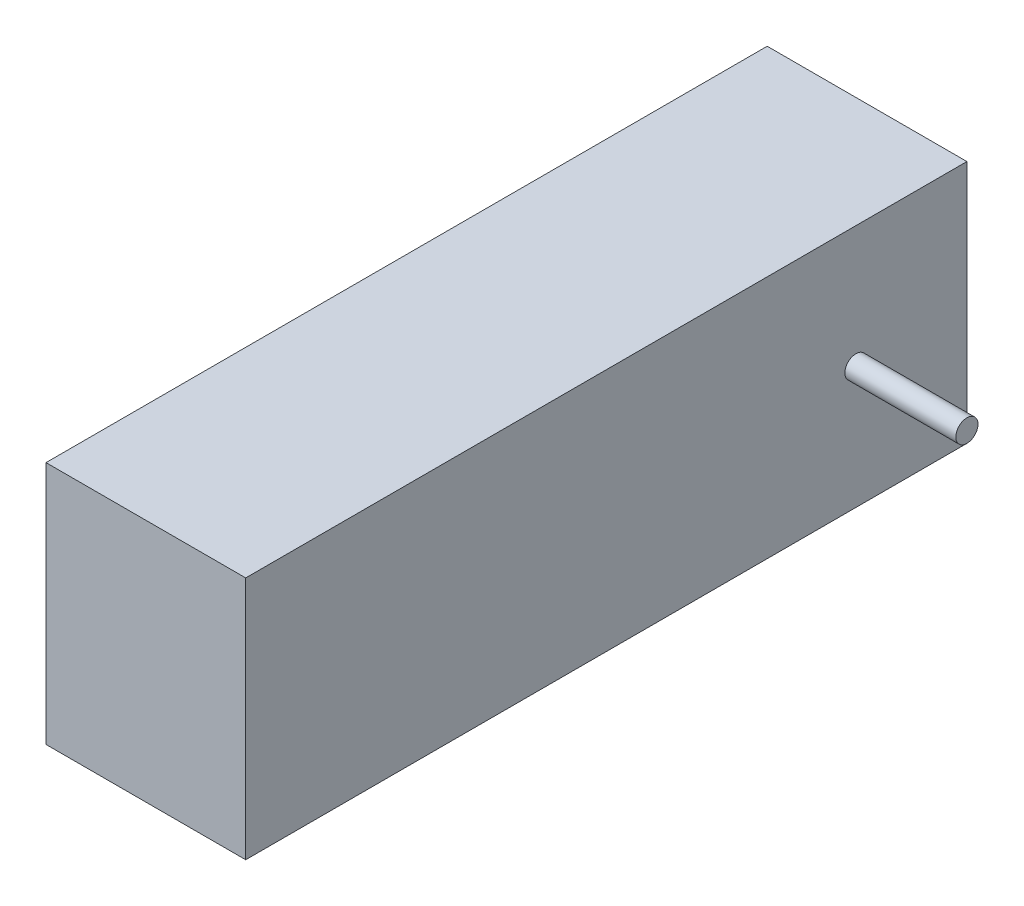
SolidWorks part; units mm, degrees
ref_plane "前基準面" through (0, 0, 0) normal (0, 0, 1) x (1, 0, 0)
ref_plane "上基準面" through (0, 0, 0) normal (0, 1, 0) x (1, 0, 0)
ref_plane "右基準面" through (0, 0, 0) normal (1, 0, 0) x (0, 0, -1)
sketch "草圖1" plane through (0, 0, 0) normal (0, 0, 1) x (1, 0, 0)
  line L1 (9, 11) -> (-9, 11)
  line L2 (9, 11) -> (9, -11)
  line L3 (9, -11) -> (-9, -11)
  line L4 (-9, 11) -> (-9, -11)
  line L5 (9, 11) -> (-9, -11) construction
  line L6 (9, -11) -> (-9, 11) construction
  point P0 (0, 0)
  dimension "D1" = 22
  dimension "D2" = 18
extrude "填料-伸長1" add sketch "草圖1" along normal blind 65
sketch "草圖2" plane through (9, 0, 0) normal (1, 0, 0) x (0, 0, -1)
  line L0 (0, -11) -> (0, 11) construction
  circle A0 centre (-10, 0) radius 1
  dimension "D2" = 2
  dimension "D1" = 10
extrude "填料-伸長2" add sketch "草圖2" along normal blind 10 and the other way blind 28
